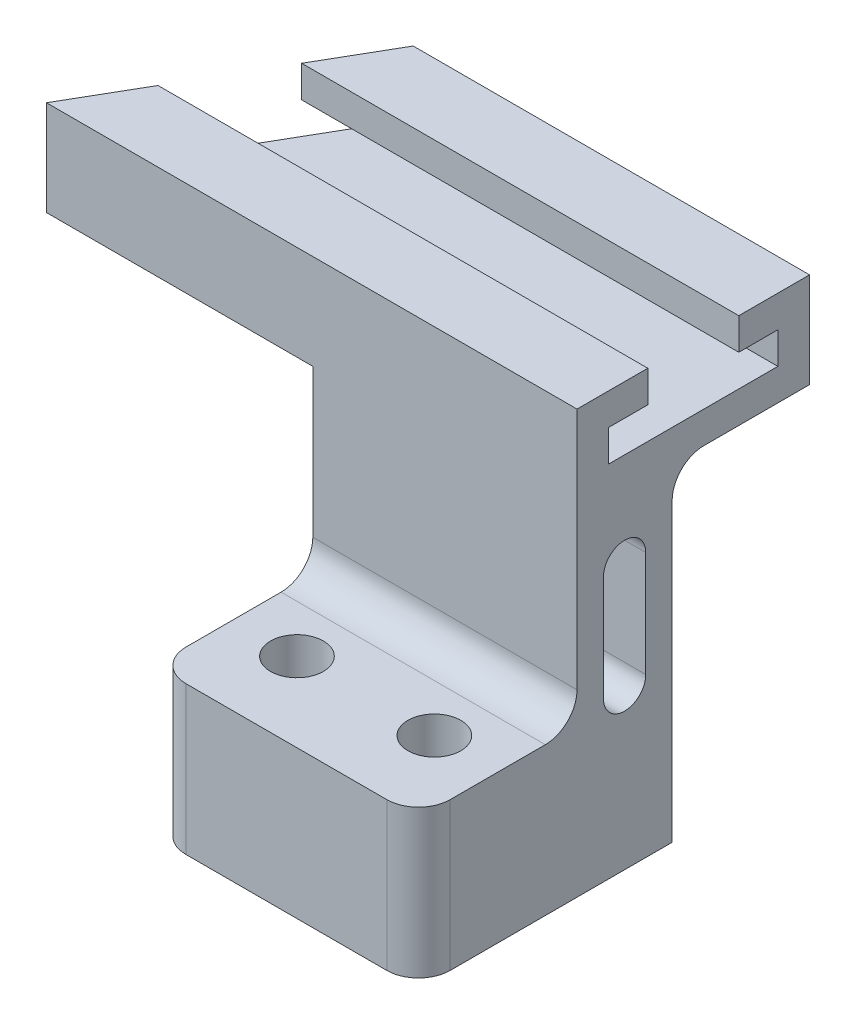
SolidWorks part; units mm, degrees
other "DetailItem1"
ref_plane "Front Plane" through (0, 0, 0) normal (0, 0, 1) x (1, 0, 0)
ref_plane "Top Plane" through (0, 0, 0) normal (0, 1, 0) x (1, 0, 0)
ref_plane "Right Plane" through (0, 0, 0) normal (1, 0, 0) x (0, 0, -1)
sketch "Sketch1" plane through (0, 0, 0) normal (1, 0, 0) x (0, 0, -1)
  line L0 (0, 0) -> (48, 0)
  line L1 (48, 0) -> (48, 56)
  line L2 (54, 62) -> (74, 62)
  line L3 (74, 62) -> (74, 80)
  line L4 (74, 80) -> (60.6154, 80)
  line L5 (60.6154, 80) -> (60.6154, 74)
  line L6 (60.6154, 74) -> (68, 74)
  line L7 (68, 74) -> (68, 68)
  line L8 (68, 68) -> (36, 68)
  line L9 (36, 68) -> (36, 74)
  line L10 (36, 74) -> (43.3846, 74)
  line L11 (43.3846, 74) -> (43.3846, 80)
  line L12 (43.3846, 80) -> (30, 80)
  line L13 (30, 80) -> (30, 34)
  line L14 (24, 28) -> (0, 28)
  line L15 (0, 28) -> (0, 0)
  line L16 (39, 50) -> (39, 30) construction
  line L17 (43, 50) -> (43, 30)
  line L18 (35, 50) -> (35, 30)
  arc A0 (43, 50) -> (35, 50) centre (39, 50) ccw
  arc A1 (35, 30) -> (43, 30) centre (39, 30) ccw
  arc A2 (30, 34) -> (24, 28) centre (24, 34) cw
  arc A3 (48, 56) -> (54, 62) centre (54, 56) cw
  point P19 (39, 40)
  dimension "D11" = 4
  dimension "D15" = 6
  dimension "D16" = 6
  dimension "D1" = 48
  dimension "D2" = 80
  dimension "D3" = 18
  dimension "D4" = 28
  dimension "D5" = 6
  dimension "D6" = 6
  dimension "D7" = 44
  dimension "D8" = 18
  dimension "D9" = 6
  dimension "D10" = 6
  dimension "D12" = 30
  dimension "D13" = 20
  dimension "D14" = 9
extrude "Boss-Extrude1" add sketch "Sketch1" against normal blind 110
sketch "Sketch2" plane through (0, 80, 0) normal (0, 1, 0) x (1, 0, 0)
  line L0 (-110, 74) -> (0, 74)
  line L1 (-75, 74) -> (-119.2602, -2.6609)
  line L2 (-110, 74) -> (-110, 13.3782)
  line L3 (-110, 43.3846) -> (-110, 30) construction
  line L4 (-75, 74) -> (-110, 74)
  line L5 (-110, 13.3782) -> (-75, 74)
  line M4 (0, 43.3846) -> (-110, 43.3846)
  line M5 (-110, 43.3846) -> (-110, 30)
  dimension "D1" = 60
  dimension "D2" = 75
extrude "Cut-Extrude1" cut sketch "Sketch2" against normal through all contours L0 L2 L1 M4 | L1 M4 M5
sketch "Sketch3" plane through (0, 0, 0) normal (0, 0, 1) x (1, 0, 0)
  line L7 (-110, 0) -> (0, 0) construction
  line L8 (-50, 0) -> (-124.7603, 0)
  line L9 (-50, 0) -> (-50, 62)
  line L10 (-50, 62) -> (-124.7603, 62)
  line L11 (-124.7603, 0) -> (-124.7603, 62)
  line L12 (-100.4034, 80) -> (0, 80) construction
  line L13 (0, 28) -> (0, 0) construction
  dimension "D1" = 18
  dimension "D2" = 50
extrude "Cut-Extrude2" cut sketch "Sketch3" against normal through all
sketch "Sketch4" plane through (0, 28, 0) normal (0, 1, 0) x (1, 0, 0)
  line L0 (-50, 0) -> (0, 0) construction
  line L1 (-50, 0) -> (-50, 24) construction
  line L2 (-50, 15) -> (0, 15) construction
  line L3 (0, 24) -> (0, 0) construction
  circle A0 centre (-38, 15) radius 5
  circle A1 centre (-12, 15) radius 5
  dimension "D1" = 10
  dimension "D2" = 15
  dimension "D3" = 12
  dimension "D4" = 2
extrude "Cut-Extrude3" cut sketch "Sketch4" against normal through all
fillet "Fillet1" radius 6 2 edges at (0, 14, 0) (-50, 14, 0)
